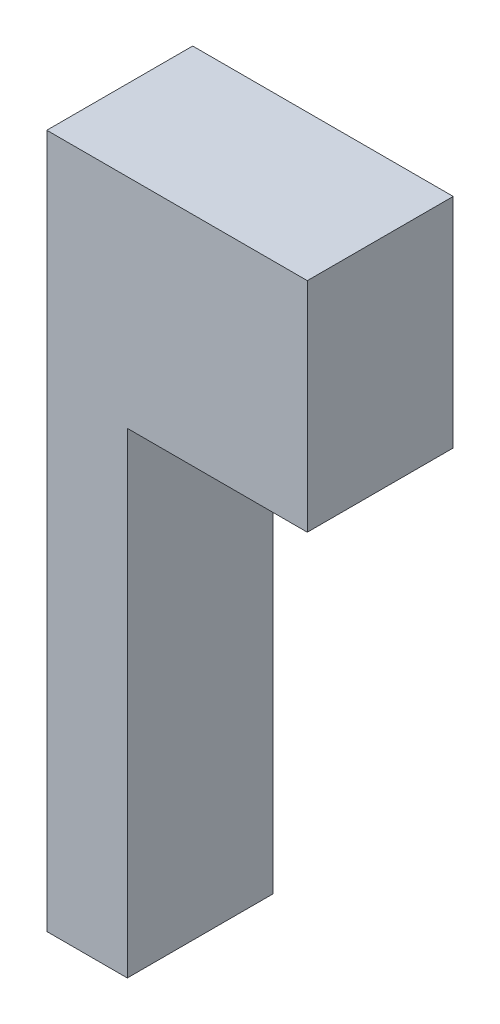
SolidWorks part; units mm, degrees
ref_plane "Front Plane" through (0, 0, 0) normal (0, 0, 1) x (1, 0, 0)
ref_plane "Top Plane" through (0, 0, 0) normal (0, 1, 0) x (1, 0, 0)
ref_plane "Right Plane" through (0, 0, 0) normal (1, 0, 0) x (0, 0, -1)
sketch "Sketch1" plane through (0, 0, 0) normal (0, 0, 1) x (1, 0, 0)
  line L1 (0, 0) -> (3.4, 0)
  line L2 (0, 0) -> (0, 20.1)
  line L3 (0, 20.1) -> (3.4, 20.1)
  line L4 (3.4, 0) -> (3.4, 20.1)
  line L5 (0, 20.1) -> (11, 20.1)
  line L6 (0, 20.1) -> (0, 29.3)
  line L7 (0, 29.3) -> (11, 29.3)
  line L8 (11, 20.1) -> (11, 29.3)
  dimension "D1" = 3.4
  dimension "D2" = 20.1
  dimension "D3" = 9.2
  dimension "D4" = 11
extrude "Boss-Extrude1" add sketch "Sketch1" along normal blind 6.16 contours L1 L4 L3 L2 | L5 L8 L7 L6
